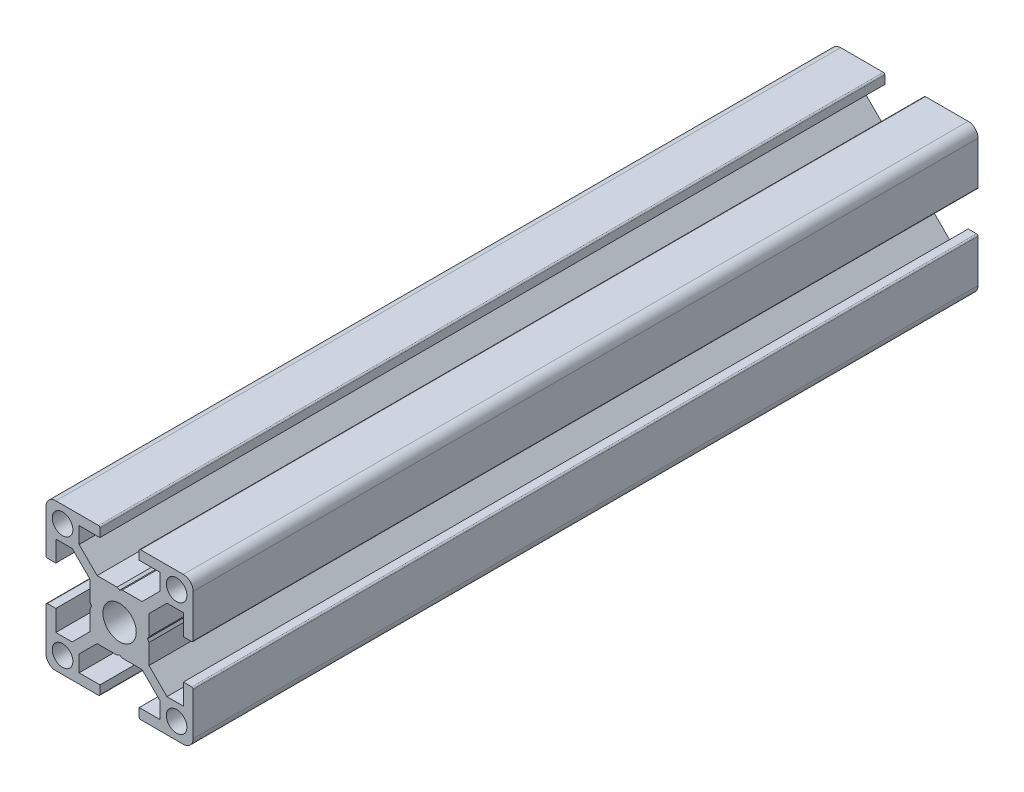
SolidWorks part; units mm, degrees
ref_plane "Front Plane" through (0, 0, 0) normal (0, 0, 1) x (1, 0, 0)
ref_plane "Top Plane" through (0, 0, 0) normal (0, 1, 0) x (1, 0, 0)
ref_plane "Right Plane" through (0, 0, 0) normal (1, 0, 0) x (0, 0, -1)
sketch "Sketch1" plane through (0, 0, 0) normal (0, 0, 1) x (1, 0, 0)
  line L0 (-14.7, 4) -> (-13, 4)
  line L1 (-13, 4) -> (-13, 8.25)
  line L2 (-13, 8.25) -> (-9.6642, 8.25)
  line L3 (-9.6642, 8.25) -> (-6, 4.5858)
  line L4 (-6, 4.5858) -> (-6, 0.5196)
  line L5 (-6, 0.5196) -> (-5.7, 0)
  line L6 (-5.7, 0) -> (-6, -0.5196)
  line L7 (-6, -0.5196) -> (-6, -4.5858)
  line L8 (-6, -4.5858) -> (-9.6642, -8.25)
  line L9 (-9.6642, -8.25) -> (-13, -8.25)
  line L10 (-13, -8.25) -> (-13, -4)
  line L11 (-13, -4) -> (-14.7, -4)
  line L12 (-15, -4.3) -> (-15, -13)
  line L13 (-13, -15) -> (-4.3, -15)
  line L14 (-4, -14.7) -> (-4, -13)
  line L15 (-4, -13) -> (-8.25, -13)
  line L16 (-8.25, -13) -> (-8.25, -9.6642)
  line L17 (-8.25, -9.6642) -> (-4.5858, -6)
  line L18 (-4.5858, -6) -> (-0.5196, -6)
  line L19 (-0.5196, -6) -> (0, -5.7)
  line L20 (0, -5.7) -> (0.5196, -6)
  line L21 (0.5196, -6) -> (4.5858, -6)
  line L22 (4.5858, -6) -> (8.25, -9.6642)
  line L23 (8.25, -9.6642) -> (8.25, -13)
  line L24 (8.25, -13) -> (4, -13)
  line L25 (4, -13) -> (4, -14.7)
  line L26 (4.3, -15) -> (13, -15)
  line L27 (15, -13) -> (15, -4.3)
  line L28 (14.7, -4) -> (13, -4)
  line L29 (13, -4) -> (13, -8.25)
  line L30 (13, -8.25) -> (9.6642, -8.25)
  line L31 (9.6642, -8.25) -> (6, -4.5858)
  line L32 (6, -4.5858) -> (6, -0.5196)
  line L33 (6, -0.5196) -> (5.7, 0)
  line L34 (5.7, 0) -> (6, 0.5196)
  line L35 (6, 0.5196) -> (6, 4.5858)
  line L36 (6, 4.5858) -> (9.6642, 8.25)
  line L37 (9.6642, 8.25) -> (13, 8.25)
  line L38 (13, 8.25) -> (13, 4)
  line L39 (13, 4) -> (14.7, 4)
  line L40 (15, 4.3) -> (15, 13)
  line L41 (13, 15) -> (4.3, 15)
  line L42 (4, 14.7) -> (4, 13)
  line L43 (4, 13) -> (8.25, 13)
  line L44 (8.25, 13) -> (8.25, 9.6642)
  line L45 (8.25, 9.6642) -> (4.5858, 6)
  line L46 (4.5858, 6) -> (0.5196, 6)
  line L47 (0.5196, 6) -> (0, 5.7)
  line L48 (0, 5.7) -> (-0.5196, 6)
  line L49 (-0.5196, 6) -> (-4.5858, 6)
  line L50 (-4.5858, 6) -> (-8.25, 9.6642)
  line L51 (-8.25, 9.6642) -> (-8.25, 13)
  line L52 (-8.25, 13) -> (-4, 13)
  line L53 (-4, 13) -> (-4, 14.7)
  line L54 (-4.3, 15) -> (-13, 15)
  line L55 (-15, 13) -> (-15, 4.3)
  arc A0 (-15, 4.3) -> (-14.7, 4) centre (-14.7, 4.3) ccw
  arc A1 (-14.7, -4) -> (-15, -4.3) centre (-14.7, -4.3) ccw
  arc A2 (-15, -13) -> (-13, -15) centre (-13, -13) ccw
  arc A3 (-4.3, -15) -> (-4, -14.7) centre (-4.3, -14.7) ccw
  arc A4 (4, -14.7) -> (4.3, -15) centre (4.3, -14.7) ccw
  arc A5 (13, -15) -> (15, -13) centre (13, -13) ccw
  arc A6 (15, -4.3) -> (14.7, -4) centre (14.7, -4.3) ccw
  arc A7 (14.7, 4) -> (15, 4.3) centre (14.7, 4.3) ccw
  arc A8 (15, 13) -> (13, 15) centre (13, 13) ccw
  arc A9 (4.3, 15) -> (4, 14.7) centre (4.3, 14.7) ccw
  arc A10 (-4, 14.7) -> (-4.3, 15) centre (-4.3, 14.7) ccw
  arc A11 (-13, 15) -> (-15, 13) centre (-13, 13) ccw
  circle A12 centre (11.625, 11.625) radius 2.1
  circle A13 centre (11.625, -11.625) radius 2.1
  circle A14 centre (0, 0) radius 3.4
  circle A15 centre (-11.625, -11.625) radius 2.1
  circle A16 centre (-11.625, 11.625) radius 2.1
extrude "Boss-Extrude1" add sketch "Sketch1" along normal blind 160
